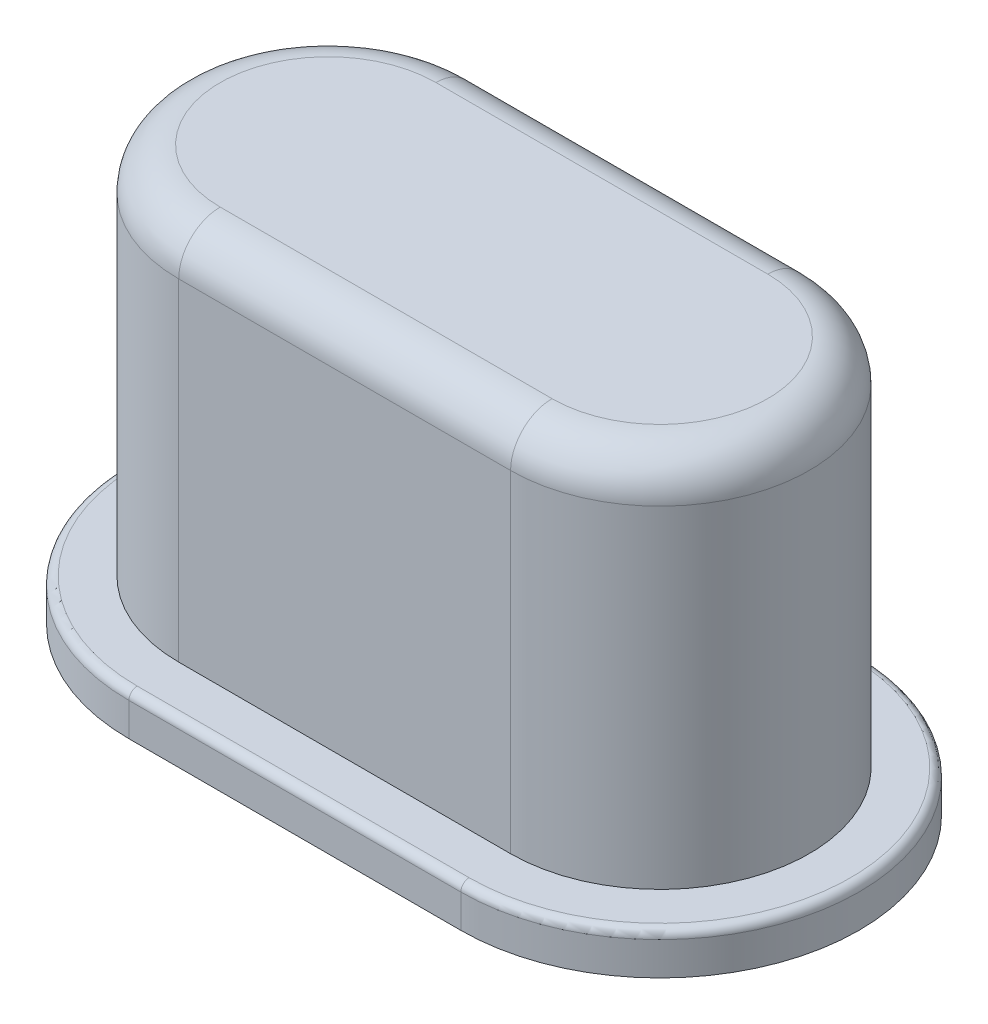
SolidWorks part; units mm, degrees
ref_plane "Front Plane" through (0, 0, 0) normal (0, 0, 1) x (1, 0, 0)
ref_plane "Top Plane" through (0, 0, 0) normal (0, 1, 0) x (1, 0, 0)
ref_plane "Right Plane" through (0, 0, 0) normal (1, 0, 0) x (0, 0, -1)
sketch "Sketch1" plane through (0, 0, 0) normal (0, 1, 0) x (1, 0, 0)
  line L0 (0, 0) -> (0, 3.1646) construction
  line L1 (2, 0) -> (-2, 0) construction
  line L2 (-2, 1.8) -> (2, 1.8)
  line L3 (0, 0) -> (0, -3.4617) construction
  line L4 (-2, -1.8) -> (2, -1.8)
  arc A0 (-2, 1.8) -> (-2, -1.8) centre (-2, 0) ccw
  arc A1 (2, 1.8) -> (2, -1.8) centre (2, 0) cw
  point P9 (0, 1.8)
  point P12 (0, -1.8)
  dimension "D1" = 3.6
  dimension "D2" = 2
extrude "Boss-Extrude1" add sketch "Sketch1" along normal blind 4.5
sketch "Sketch2" plane through (0, 0, 0) normal (0, -1, 0) x (1, 0, 0)
  line L12 (-2, -2.4) -> (2, -2.4)
  line L13 (2, 2.4) -> (-2, 2.4)
  line L14 (-2, -2.4) -> (2, -2.4)
  line L15 (2, 2.4) -> (-2, 2.4)
  arc A10 (-2, 2.4) -> (-2, -2.4) centre (-2, 0) ccw
  arc A11 (2, -2.4) -> (2, 2.4) centre (2, 0) ccw
  arc A12 (-2, 2.4) -> (-2, -2.4) centre (-2, 0) ccw
  arc A13 (2, -2.4) -> (2, 2.4) centre (2, 0) ccw
  arc M6 (-2, 1.8) -> (-2, -1.8) centre (-2, 0) ccw
  line M7 (-2, -1.8) -> (2, -1.8)
  arc M8 (2, -1.8) -> (2, 1.8) centre (2, 0) ccw
  line M9 (2, 1.8) -> (-2, 1.8)
  dimension "D2" = 0.6
extrude "Boss-Extrude2" add sketch "Sketch2" along normal blind 0.5 contours L14 A13 L15 A12 M6 M9 M8 M7 | M9 M6 M7 M8
fillet "Fillet1" radius 0.5 4 edges at (-3.8, 4.5, 0) (0, 4.5, -1.8) (3.8, 4.5, 0) (0, 4.5, 1.8)
fillet "Fillet2" radius 0.1 4 edges at (4.4, 0, 0) (0, 0, -2.4) (-4.4, 0, 0) (0, 0, 2.4)
